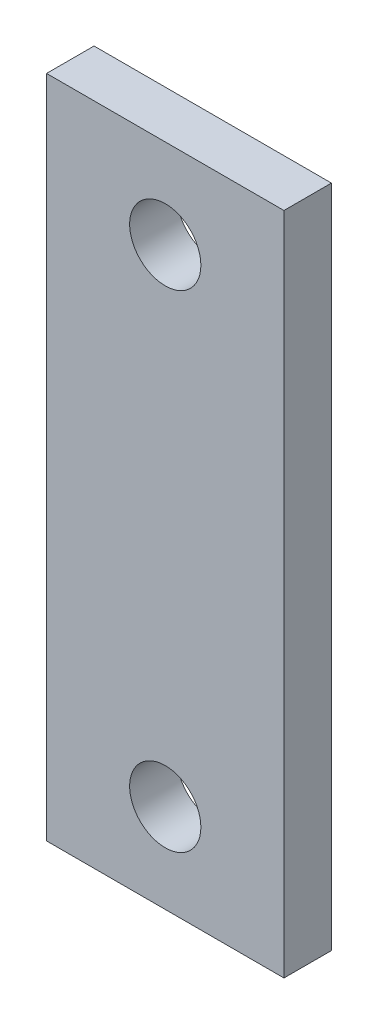
SolidWorks part; units mm, degrees
ref_plane "Front Plane" through (0, 0, 0) normal (0, 0, 1) x (1, 0, 0)
ref_plane "Top Plane" through (0, 0, 0) normal (0, 1, 0) x (1, 0, 0)
ref_plane "Right Plane" through (0, 0, 0) normal (1, 0, 0) x (0, 0, -1)
sketch "Sketch1" plane through (0, 0, 0) normal (0, 0, 1) x (1, 0, 0)
  line L0 (15.2003, 13.7604) -> (0.2003, 13.7604)
  line L1 (-4.7997, -6.2396) -> (0.2003, -6.2396)
  line L2 (-4.7997, -6.2396) -> (-4.7997, 19.7604)
  line L3 (-4.7997, 19.7604) -> (15.2003, 19.7604)
  line L4 (15.2003, 13.7604) -> (15.2003, 19.7604)
  line L5 (-4.7997, -6.2396) -> (15.2003, 19.7604) construction
  line L6 (-4.7997, 19.7604) -> (0, 0) construction
  line L7 (0.2003, 13.7604) -> (0.2003, -6.2396)
  point P0 (0, 0)
  dimension "D1" = 6
  dimension "D2" = 5
  dimension "D3" = 20
  dimension "D4" = 15
extrude "Boss-Extrude1" add sketch "Sketch1" along normal blind 35
sketch "Sketch2" plane through (-4.7997, 0, 0) normal (-1, 0, 0) x (0, 0, 1)
  line L0 (0, 19.7604) -> (4, 19.7604)
  line L1 (35, 19.7604) -> (0, 19.7604) construction
  line L2 (4, 19.7604) -> (4, -6.2396)
  line L3 (35, -6.2396) -> (0, -6.2396) construction
  line L4 (4, -6.2396) -> (0, -6.2396)
  line L5 (0, 19.7604) -> (0, -6.2396)
  dimension "D1" = 4
sketch "Sketch3" plane through (0, 13.7604, 0) normal (0, -1, 0) x (1, 0, 0)
  line L0 (0.2003, 35) -> (15.2003, 35) construction
  line L1 (15.2003, 35) -> (15.2003, 0) construction
  circle A0 centre (7.7003, 29) radius 1.5
  circle A1 centre (7.7003, 22) radius 1.5
  circle A2 centre (7.7003, 15) radius 1.5
  dimension "D1" = 3
  dimension "D2" = 6
  dimension "D3" = 7.5
  dimension "D4" = 3
extrude "Cut-Extrude1" cut sketch "Sketch3" against normal blind 15
extrude "Boss-Extrude2" add sketch "Sketch2" against normal up to surface (20 mm away) up to face at (15.2003, 16.7604, 17.5)
sketch "Sketch5" plane through (0, 19.7604, 0) normal (0, 1, 0) x (1, 0, 0)
  line L0 (0.2003, -4) -> (-4.7997, -4)
  line L6 (-4.7997, 0) -> (-4.7997, -35)
  line L7 (15.2003, 0) -> (-4.7997, 0)
  line L8 (15.2003, -4) -> (15.2003, 0)
  line L9 (0.2003, -4) -> (15.2003, -4)
  line L10 (0.2003, -35) -> (0.2003, -4)
  line L11 (-4.7997, -35) -> (0.2003, -35)
  line L12 (-4.7997, 0) -> (-4.7997, -35)
  line L13 (15.2003, 0) -> (-4.7997, 0)
  line L14 (15.2003, -4) -> (15.2003, 0)
  line L15 (0.2003, -4) -> (15.2003, -4)
  line L17 (-4.7997, -35) -> (0.2003, -35)
  line M8 (15.2003, -35) -> (15.2003, 0)
  line M9 (15.2003, 0) -> (-4.7997, 0)
  line M10 (-4.7997, 0) -> (-4.7997, -35)
  dimension "D1" = 0
extrude "Boss-Extrude3" add sketch "Sketch5" along normal blind 15 contours L0 L15 M8 M9 M10
ref_plane "Plane1" through (0, 6.7604, 0) normal (0, 1, 0) x (1, 0, 0)
mirror "Mirror1" about plane through (0, 6.7604, 0) normal (0, 1, 0) of "Boss-Extrude3"
sketch "Sketch6" plane through (0, 0, 4) normal (0, 0, 1) x (1, 0, 0)
  line L0 (5.2003, -21.2396) -> (5.2003, 34.7604) construction
  line L1 (15.2003, -21.2396) -> (-4.7997, -21.2396) construction
  line L2 (15.2003, 34.7604) -> (-4.7997, 34.7604) construction
  line L3 (0.2003, -6.2396) -> (-4.7997, -6.2396) construction
  line L4 (15.2003, 19.7604) -> (-4.7997, 19.7604) construction
  circle A0 centre (5.2003, -13.7396) radius 3
  circle A1 centre (5.2003, 27.2604) radius 3
  point P12 (-2.2997, -6.2396)
  dimension "D1" = 6
  dimension "D2" = 6
  dimension "D3" = 7.5
  dimension "D4" = 7.5
extrude "Cut-Extrude2" cut sketch "Sketch6" against normal blind 15
sketch "Sketch7" plane through (0, 0, 4) normal (0, 0, 1) x (1, 0, 0)
  line L0 (0.2003, -6.2396) -> (15.2003, -6.2396)
  line L1 (15.2003, 13.7604) -> (15.2003, -21.2396) construction
  line L2 (15.2003, -6.2396) -> (15.2003, -1.2396)
  line L3 (15.2003, -1.2396) -> (0.2003, -1.2396)
  line L4 (0.2003, -6.2396) -> (0.2003, 13.7604) construction
  line L5 (0.2003, -1.2396) -> (0.2003, -6.2396)
  dimension "D1" = 5
extrude "Boss-Extrude4" add sketch "Sketch7" along normal up to surface (31 mm away) up to face at (3.5337, 9.0938, 35)
sketch "Sketch8" plane through (0, 0, 35) normal (0, 0, 1) x (1, 0, 0)
  line L8 (15.2003, 13.7604) -> (15.2003, 19.7604)
  line L9 (15.2003, 19.7604) -> (-4.7997, 19.7604)
  line L10 (-4.7997, 19.7604) -> (-4.7997, -6.2396)
  line L11 (-4.7997, -6.2396) -> (15.2003, -6.2396)
  line L12 (15.2003, -6.2396) -> (15.2003, -1.2396)
  line L13 (15.2003, -1.2396) -> (0.2003, -1.2396)
  line L14 (0.2003, -1.2396) -> (0.2003, 13.7604)
  line L15 (0.2003, 13.7604) -> (15.2003, 13.7604)
  line L16 (15.2003, 13.7604) -> (15.2003, 19.7604)
  line L17 (15.2003, 19.7604) -> (-4.7997, 19.7604)
  line L18 (-4.7997, 19.7604) -> (-4.7997, -6.2396)
  line L19 (-4.7997, -6.2396) -> (15.2003, -6.2396)
  line L20 (15.2003, -6.2396) -> (15.2003, -1.2396)
  line L21 (15.2003, -1.2396) -> (0.2003, -1.2396)
  line L22 (0.2003, -1.2396) -> (0.2003, 13.7604)
  line L23 (0.2003, 13.7604) -> (15.2003, 13.7604)
  dimension "D1" = 0
extrude "Cut-Extrude3" cut sketch "Sketch8" against normal up to surface (31 mm away) up to face at (8.2003, -13.7396, 4)
